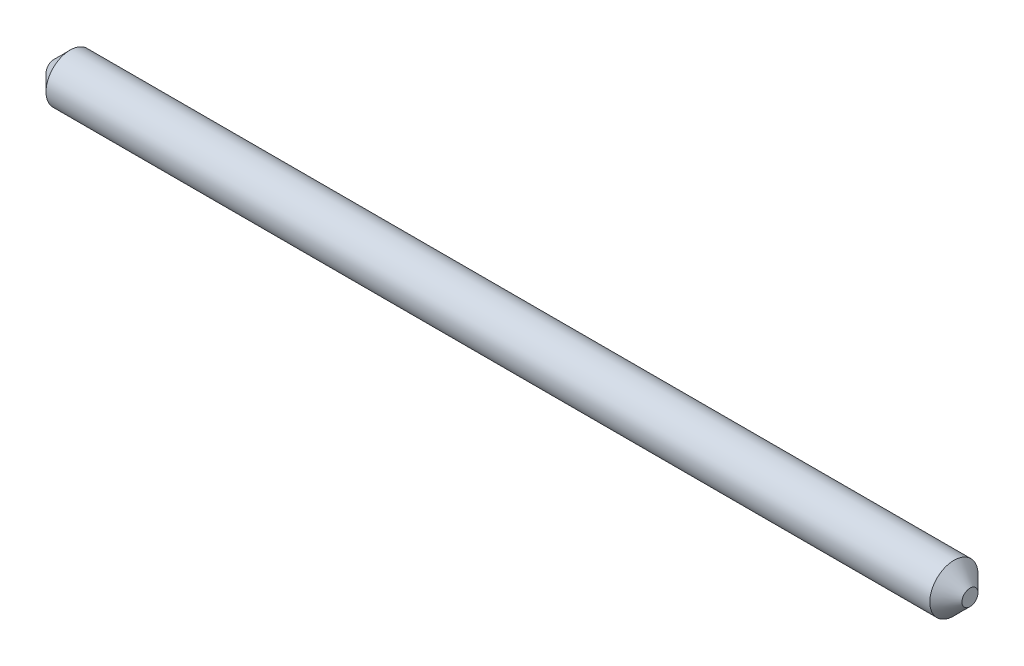
SolidWorks part; units mm, degrees
ref_plane "Front Plane" through (0, 0, 0) normal (0, 0, 1) x (1, 0, 0)
ref_plane "Top Plane" through (0, 0, 0) normal (0, 1, 0) x (1, 0, 0)
ref_plane "Right Plane" through (0, 0, 0) normal (1, 0, 0) x (0, 0, -1)
sketch "Sketch1" plane through (0, 0, 0) normal (1, 0, 0) x (0, 0, -1)
  circle A0 centre (0, 0) radius 1.5
  dimension "D1" = 3
extrude "Boss-Extrude1" add sketch "Sketch1" along normal mid plane 57
chamfer "Chamfer1" distance 1 angle 45 2 edges at (-28.5, 0, -1.5) (28.5, 0, -1.5)
